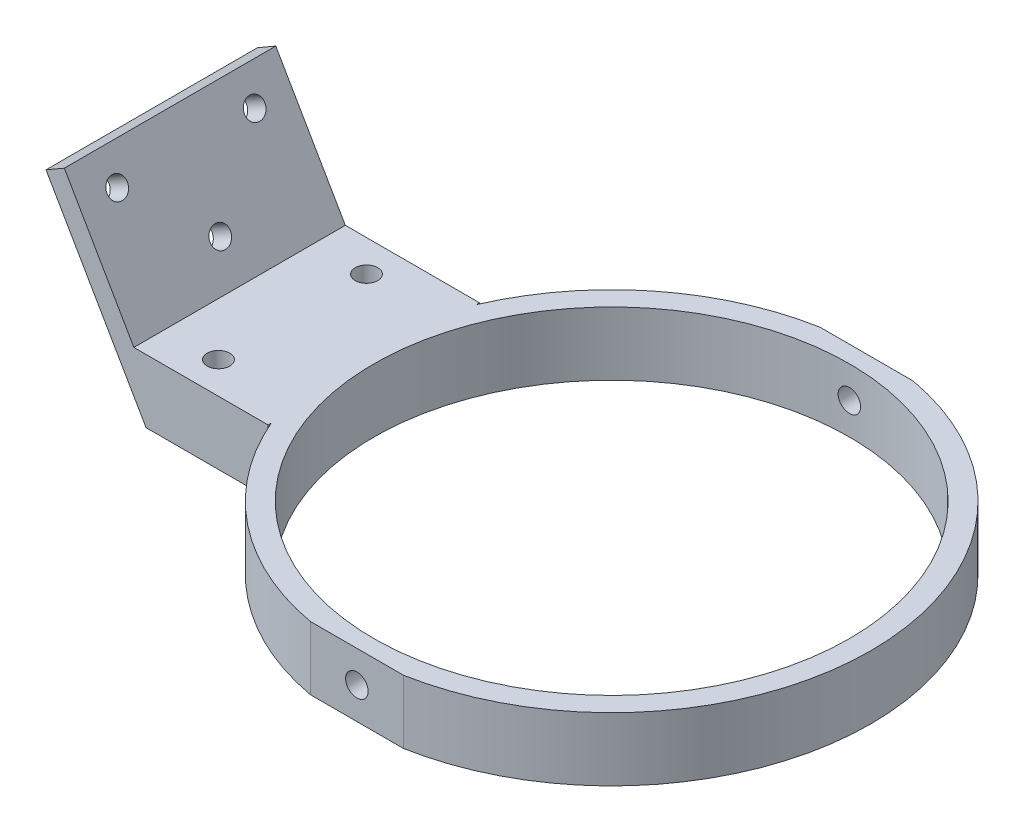
SolidWorks part; units mm, degrees
ref_plane "Front Plane" through (0, 0, 0) normal (0, 0, 1) x (1, 0, 0)
ref_plane "Top Plane" through (0, 0, 0) normal (0, 1, 0) x (1, 0, 0)
ref_plane "Right Plane" through (0, 0, 0) normal (1, 0, 0) x (0, 0, -1)
sketch "Sketch1" plane through (0, 0, 0) normal (0, 1, 0) x (1, 0, 0)
  circle A0 centre (0, 0) radius 29.845
  dimension "D1" = 59.69
extrude "Extrude-Thin1" add sketch "Sketch1" along normal blind 7.62 thin thin type two direction wall 1.27 second wall 1.27
sketch "Sketch2" plane through (0, 7.62, 0) normal (0, 1, 0) x (1, 0, 0)
  line L0 (-28.575, 0) -> (-28.575, -12.7)
  line L1 (-28.575, -12.7) -> (-47.625, -12.7)
  line L2 (-47.625, 12.7) -> (-47.625, -12.7)
  line L6 (-28.575, 0) -> (-28.575, 12.7)
  line L7 (-28.575, 12.7) -> (-47.625, 12.7)
  circle A1 centre (0, 0) radius 28.575 construction
  dimension "D1" = 12.7
  dimension "D2" = 12.7
  dimension "D3" = 19.05
extrude "Boss-Extrude1" add sketch "Sketch2" against normal blind 7.62 contours L7 L2 L1 L0 L6
sketch "Sketch3" plane through (0, 0, 12.7) normal (0, 0, 1) x (1, 0, 0)
  line L0 (-47.625, 0) -> (-43.2256, 0)
  line L1 (-28.575, 0) -> (-47.625, 0) construction
  line L2 (-43.2256, 0) -> (-47.625, 7.62)
  line L3 (-47.625, 7.62) -> (-47.625, 0)
  dimension "D1" = 30
extrude "Cut-Extrude1" cut sketch "Sketch3" against normal up to next and the other way through all
sketch "Sketch4" plane through (-32.4192, -18.7172, 0) normal (-0.866, -0.5, 0) x (0, 0, 1)
  line L1 (-12.7, 30.4116) -> (12.7, 30.4116) construction
  line L4 (-12.7, 21.6128) -> (12.7, 21.6128)
  line L6 (-12.7, 21.6128) -> (-12.7, 45.6516)
  line L7 (-12.7, 45.6516) -> (12.7, 45.6516)
  line L8 (12.7, 21.6128) -> (12.7, 45.6516)
  dimension "D1" = 15.24
  dimension "D2" = 25.4
extrude "Boss-Extrude2" add sketch "Sketch4" against normal blind 2.54 contours L6 L7 L8 L4
hole_wizard "#2 Clearance Hole1" positions "Sketch6" profile "Sketch5" hole size "#2" standard "ANSI Inch" end condition through all
sketch "Sketch6" plane through (-30.2195, -17.4472, 0) normal (0.866, 0.5, 0) x (0, 0, -1)
  line L0 (12.7, 28.9451) -> (12.7, 45.6516) construction
  line L3 (12.7, 45.6516) -> (-12.7, 45.6516) construction
  line L4 (-12.7, 28.9451) -> (-12.7, 45.6516) construction
  point P0 (-8.255, 41.8416)
  point P2 (8.255, 41.8416)
  point P15 (0, 33.5866)
  dimension "D1" = 16.51
  dimension "D2" = 4.445
  dimension "D3" = 3.81
  dimension "D4" = 12.7
  dimension "D5" = 8.255
  dimension "D6" = 3.81
sketch "Sketch5" plane through (-51.1403, 18.7887, 8.255) normal (0, 0, 1) x (-0.5, 0.866, 0)
  line L0 (0, 0) -> (0, 12.9491)
  line L1 (0, 12.9491) -> (1.2192, 12.9491)
  line L2 (1.2192, 12.9491) -> (1.2192, 0)
  line L5 (1.2192, 0) -> (0, 0)
  line L11 (0, -6.35) -> (0, 107.95) construction
  dimension "Thru Hole Dia." = 2.4384
  dimension "Thru Hole Depth" = 12.9491
hole_wizard "#6-32 Tapped Hole1" positions "Sketch8" profile "Sketch7" tap size "#6-32" standard "ANSI Inch" end condition through all
sketch "Sketch8" plane through (0, 7.62, 0) normal (0, 1, 0) x (1, 0, 0)
  line L0 (-44.6921, 12.7) -> (-44.6921, -12.7) construction
  line L1 (-28.575, 12.7) -> (-44.6921, 12.7) construction
  line L4 (-28.575, -12.7) -> (-44.6921, -12.7) construction
  point P0 (-38.3421, -8.89)
  point P2 (-38.3421, 8.89)
  dimension "D1" = 6.35
  dimension "D2" = 6.35
  dimension "D3" = 3.81
  dimension "D4" = 3.81
sketch "Sketch7" plane through (-38.3421, 7.62, 8.89) normal (1, 0, 0) x (0, 0, 1)
  line L0 (0, 0) -> (0, 7.62)
  line L1 (0, 7.62) -> (1.3525, 7.62)
  line L2 (1.3525, 7.62) -> (1.3525, 0)
  line L5 (1.3525, 0) -> (0, 0)
  line L11 (0, -6.35) -> (0, 107.95) construction
  dimension "Thru Tap Drill Dia." = 2.7051
  dimension "Thru Tap Drill Depth" = 7.62
cosmetic thread "Hole Thread1" parameters "D2"=3.5052
cosmetic thread "Hole Thread2" parameters "D2"=3.5052
sketch "Sketch9" plane through (0, 7.62, 0) normal (0, 1, 0) x (1, 0, 0)
  line L0 (-10.16, 30.607) -> (10.16, 30.607)
  line L4 (10.16, 31.115) -> (10.16, 30.607)
  line L5 (-10.16, 30.607) -> (-10.16, 31.115)
  line L6 (-10.16, 31.115) -> (10.16, 31.115)
  dimension "D1" = 20.32
  dimension "D3" = 0.508
extrude "Cut-Extrude2" cut sketch "Sketch9" against normal through all
sketch "Sketch10" plane through (0, 7.62, 0) normal (0, 1, 0) x (1, 0, 0)
  line L0 (0, -31.115) -> (14.7426, -31.115)
  line L1 (14.7426, -31.115) -> (14.7426, -30.607)
  line L2 (14.7426, -30.607) -> (-16.08, -30.607)
  line L3 (-16.08, -30.607) -> (-16.08, -31.115)
  line L4 (-16.08, -31.115) -> (0, -31.115)
  arc A0 (-28.575, -12.3131) -> (5.5995, 30.607) centre (0, 0) ccw construction
  dimension "D1" = 0.508
extrude "Cut-Extrude3" cut sketch "Sketch10" against normal through all
hole_wizard "#6-32 Tapped Hole2" positions "Sketch12" profile "Sketch11" tap size "#6-32" standard "ANSI Inch"
sketch "Sketch12" plane through (0, 0, -30.607) normal (0, 0, -1) x (-1, 0, 0)
  line L0 (5.5995, 7.62) -> (-5.5995, 7.62) construction
  point P0 (0, 3.81)
  dimension "D1" = 3.81
sketch "Sketch11" plane through (0, 3.81, -30.607) normal (1, 0, 0) x (0, 1, 0)
  line L0 (0, 0) -> (0, 11.9887)
  line L1 (0, 11.9887) -> (1.3525, 11.176)
  line L2 (1.3525, 11.176) -> (1.3525, 0)
  line L5 (1.3525, 0) -> (0, 0)
  line L10 (0, 11.9887) -> (-1.3525, 11.176) construction
  line L11 (0, -6.35) -> (0, 107.95) construction
  dimension "Tap Drill Dia." = 2.7051
  dimension "Tap Drill Depth" = 11.176
  dimension "Drill Angle" = 118
cosmetic thread "Hole Thread3" parameters "D1"=2.064, "D2"=3.5052
hole_wizard "#6-32 Tapped Hole3" positions "Sketch14" profile "Sketch13" tap size "#6-32" standard "ANSI Inch"
sketch "Sketch14" plane through (0, 0, 30.607) normal (0, 0, 1) x (1, 0, 0)
  line L0 (5.5995, 7.62) -> (-5.5995, 7.62) construction
  point P8 (0, 3.81)
  dimension "D1" = 3.81
sketch "Sketch13" plane through (0, 3.81, 30.607) normal (1, 0, 0) x (0, -1, 0)
  line L0 (0, 0) -> (0, 11.9887)
  line L1 (0, 11.9887) -> (1.3525, 11.176)
  line L2 (1.3525, 11.176) -> (1.3525, 0)
  line L5 (1.3525, 0) -> (0, 0)
  line L10 (0, 11.9887) -> (-1.3525, 11.176) construction
  line L11 (0, -6.35) -> (0, 107.95) construction
  dimension "Tap Drill Dia." = 2.7051
  dimension "Tap Drill Depth" = 11.176
  dimension "Drill Angle" = 118
cosmetic thread "Hole Thread4" parameters "D1"=2.064, "D2"=3.5052
